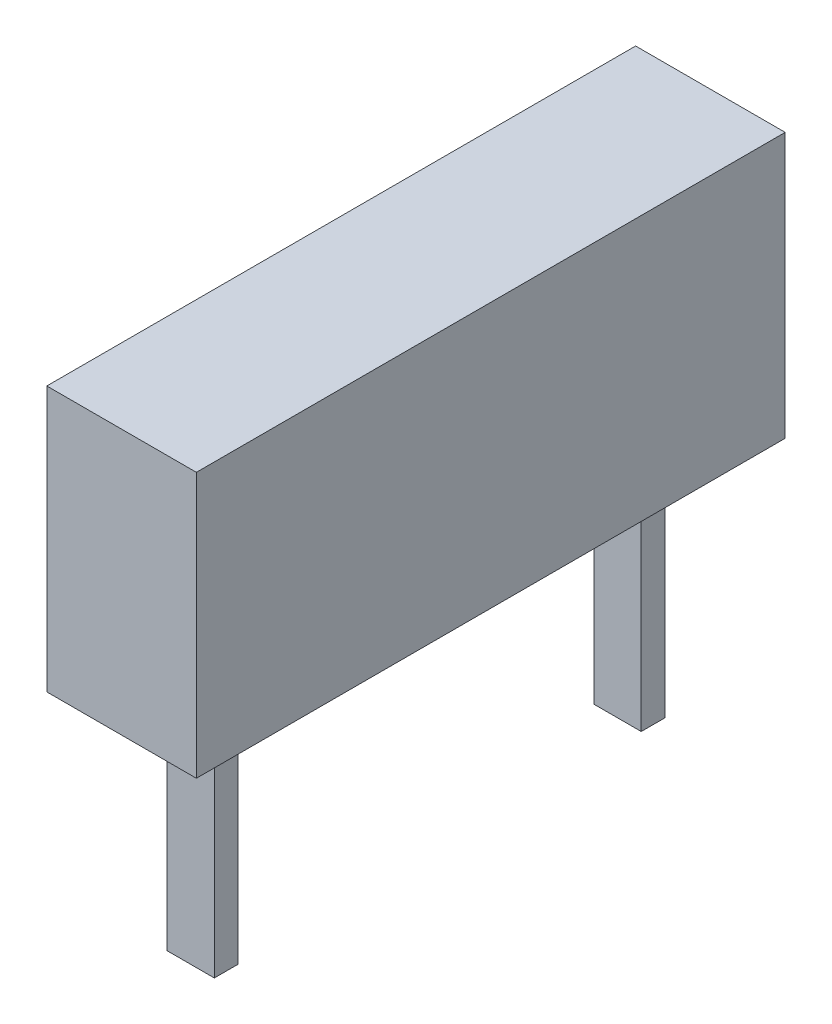
SolidWorks part; units mm, degrees
ref_plane "前视基准面" through (0, 0, 0) normal (0, 0, 1) x (1, 0, 0)
ref_plane "上视基准面" through (0, 0, 0) normal (0, 1, 0) x (1, 0, 0)
ref_plane "右视基准面" through (0, 0, 0) normal (1, 0, 0) x (0, 0, -1)
sketch "草图1" plane through (0, 0, 0) normal (0, 1, 0) x (1, 0, 0)
  line L0 (-25.8641, 0) -> (23.6912, 0) construction
  line L1 (-1.27, 5) -> (1.27, 5)
  line L2 (-1.27, 5) -> (-1.27, -5)
  line L3 (-1.27, -5) -> (1.27, -5)
  line L4 (1.27, 5) -> (1.27, -5)
  line L5 (0, 27.0034) -> (0, -30.5011) construction
  dimension "D1" = 2.54
  dimension "D2" = 10
extrude "拉伸1" add sketch "草图1" along normal blind 4.5
sketch "草图2" plane through (0, 0, 0) normal (0, -1, 0) x (1, 0, 0)
  line L0 (2.8061, 0) -> (-3.1888, 0) construction
  line L1 (0, 5.8742) -> (0, -5.9421) construction
  line L2 (1.1049, 3.625) -> (-0.8597, 3.625) construction
  line L3 (0.4, 3.825) -> (-0.4, 3.825)
  line L4 (0.4, 3.825) -> (0.4, 3.425)
  line L5 (0.4, 3.425) -> (-0.4, 3.425)
  line L6 (-0.4, 3.825) -> (-0.4, 3.425)
  line L7 (1.1049, -3.625) -> (-0.8597, -3.625) construction
  line L8 (-0.4, -3.825) -> (-0.4, -3.425)
  line L9 (0.4, -3.425) -> (-0.4, -3.425)
  line L10 (0.4, -3.825) -> (0.4, -3.425)
  line L11 (0.4, -3.825) -> (-0.4, -3.825)
  dimension "D1" = 0.4
  dimension "D2" = 0.8
  dimension "D3" = 7.25
extrude "拉伸2" add sketch "草图2" along normal blind 3.96
